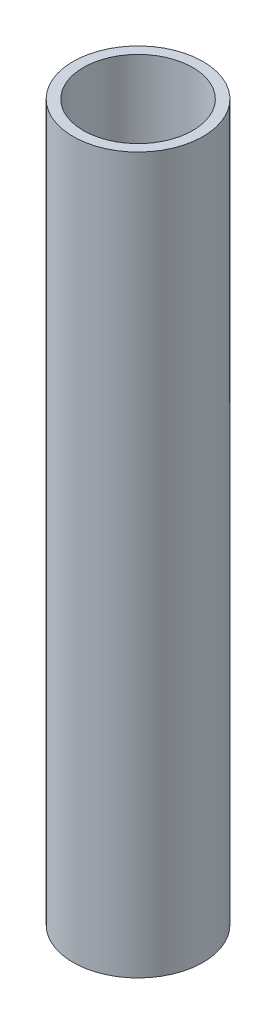
SolidWorks part; units mm, degrees
material "ｶﾞﾗｽ"
ref_plane "正面" through (0, 0, 0) normal (0, 0, 1) x (1, 0, 0)
ref_plane "平面" through (0, 0, 0) normal (0, 1, 0) x (1, 0, 0)
ref_plane "右側面" through (0, 0, 0) normal (1, 0, 0) x (0, 0, -1)
sketch "ｽｹｯﾁ1" plane through (0, 0, 0) normal (0, 1, 0) x (1, 0, 0)
  circle A0 centre (0, 0) radius 9.45
  dimension "D1" = 18.9
extrude "ﾎﾞｽ - 押し出し1" add sketch "ｽｹｯﾁ1" along normal blind 104
sketch "ｽｹｯﾁ2" plane through (0, 104, 0) normal (0, 1, 0) x (1, 0, 0)
  circle A0 centre (0, 0) radius 7.95
  dimension "D1" = 15.9
extrude "ｶｯﾄ - 押し出し1" cut sketch "ｽｹｯﾁ2" against normal blind 103 contours A0
